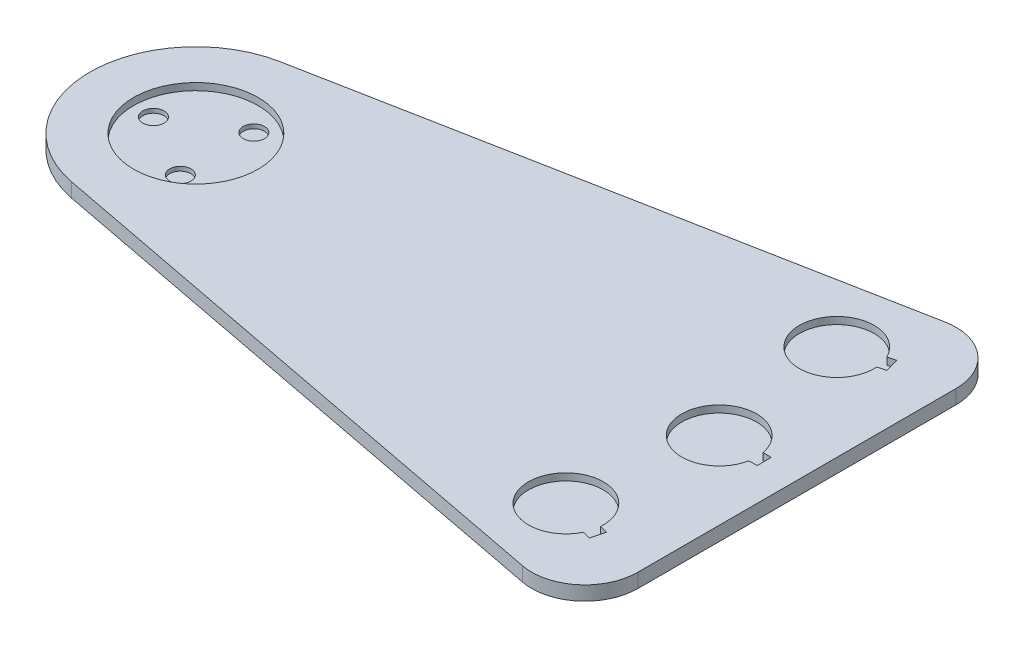
SolidWorks part; units mm, degrees
material "ABS"
ref_plane "Ön Düzlem" through (0, 0, 0) normal (0, 0, 1) x (1, 0, 0)
ref_plane "Üst Düzlem" through (0, 0, 0) normal (0, 1, 0) x (1, 0, 0)
ref_plane "Sağ Düzlem" through (0, 0, 0) normal (1, 0, 0) x (0, 0, -1)
sketch "Çizim2" plane through (0, 0, 0) normal (0, 1, 0) x (1, 0, 0)
  line L1 (-250, 150) -> (250, 150)
  line L2 (-250, 150) -> (-250, -150)
  line L3 (-250, -150) -> (250, -150)
  line L4 (250, 150) -> (250, -150)
  line L5 (-250, 150) -> (250, -150) construction
  line L6 (-250, -150) -> (250, 150) construction
  point P0 (0, 0)
  dimension "D1" = 500
  dimension "D2" = 300
extrude "Yükseklik-Ekstrüzyon2" add sketch "Çizim2" along normal blind 10
sketch "Çizim3" plane through (0, 10, 0) normal (0, 1, 0) x (1, 0, 0)
  line L0 (250, -150) -> (250, 150) construction
  line L1 (250, 150) -> (-250, 150) construction
  line L2 (-250, -150) -> (250, -150) construction
  line L3 (-250, 150) -> (-250, -150) construction
  line L4 (-189.1264, 73.6576) -> (205.4368, 149.3288)
  line L5 (-189.1264, -73.6576) -> (205.4368, -149.3288)
  line L6 (250, 112.5) -> (250, -112.5)
  arc A0 (250, 112.5) -> (205.4368, 149.3288) centre (212.5, 112.5) ccw
  arc A1 (205.4368, -149.3288) -> (250, -112.5) centre (212.5, -112.5) ccw
  arc A2 (-189.1264, 73.6576) -> (-189.1264, -73.6576) centre (-175, 0) ccw
  dimension "D1" = 150
  dimension "D2" = 150
  dimension "D3" = 75
extrude "Kes-Ekstrüzyon1" cut sketch "Çizim3" against normal blind 10 flip side to cut
sketch "Çizim6" plane through (0, 10, 0) normal (0, 1, 0) x (1, 0, 0)
  line L1 (206.85, 5) -> (226.85, 5)
  line L2 (206.85, 5) -> (206.85, -5)
  line L3 (206.85, -5) -> (226.85, -5)
  line L4 (226.85, 5) -> (226.85, -5)
  line L5 (206.85, 5) -> (226.85, -5) construction
  line L6 (206.85, -5) -> (226.85, 5) construction
  circle A0 centre (195, 0) radius 26.46
  arc A1 (-189.1264, 73.6576) -> (-189.1264, -73.6576) centre (-175, 0) ccw construction
  point P2 (216.85, 0)
  point P10 (0, 0)
  dimension "D1" = 52.92
  dimension "D4" = 370
  dimension "D2" = 10
  dimension "D3" = 31.85
  dimension "D5" = 20
extrude "Tabaklari-uzaklastirma-2" cut sketch "Çizim6" against normal blind 5 contours A0 L3 L4 L1 | L1 A0 L3 L2 | L3 A0 L1 L2
pattern_circular "Dairesel Kaplama1" count 2 every 15 about axis through (-175, 0, 0) along (0, 1, 0) of "Tabaklari-uzaklastirma-2"
mirror "Aynalama1" about plane through (0, 0, 0) normal (0, 0, 1) of "Dairesel Kaplama1"
sketch "Çizim9" plane through (0, 10, 0) normal (0, 1, 0) x (1, 0, 0)
  circle A0 centre (-175, 0) radius 44 construction
  circle A1 centre (-205, 0) radius 7.5
  dimension "D1" = 88
  dimension "D2" = 15
  dimension "D3" = 30
extrude "Kes-Ekstrüzyon4" cut sketch "Çizim9" against normal blind 8
pattern_circular "Dairesel Kaplama2" count 3 over 360 about axis through (-175, 0, 0) along (0, 1, 0) of "Kes-Ekstrüzyon4"
sketch "Çizim10" plane through (0, 10, 0) normal (0, 1, 0) x (1, 0, 0)
  circle A0 centre (-175, 0) radius 44
  dimension "D1" = 88
extrude "Kes-Ekstrüzyon5" cut sketch "Çizim10" against normal blind 5
